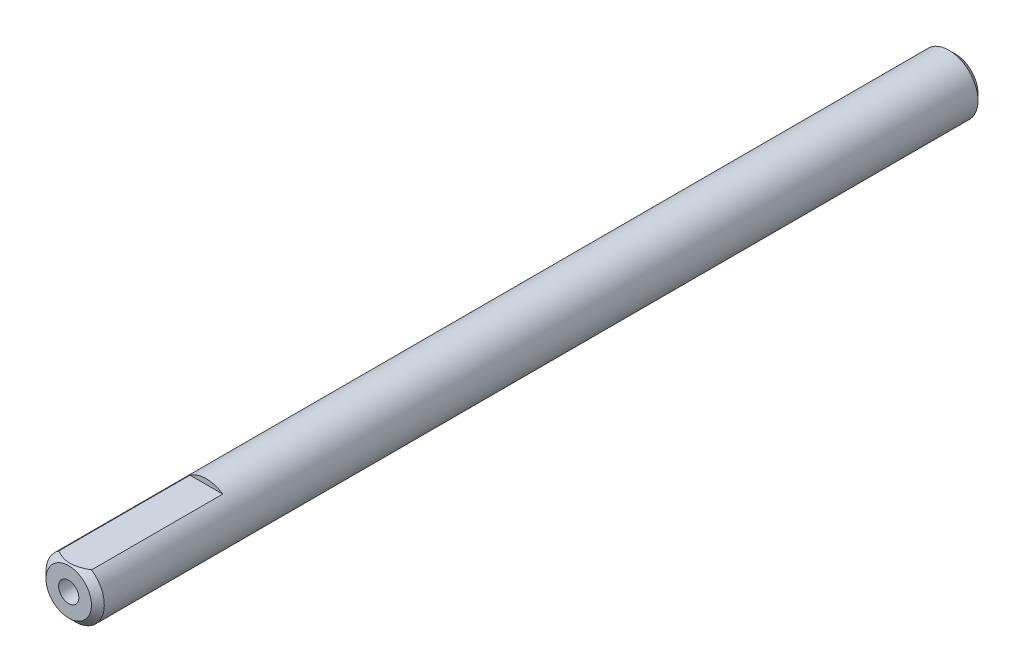
SolidWorks part; units mm, degrees
ref_plane "Ön Düzlem" through (0, 0, 0) normal (0, 0, 1) x (1, 0, 0)
ref_plane "Üst Düzlem" through (0, 0, 0) normal (0, 1, 0) x (1, 0, 0)
ref_plane "Sağ Düzlem" through (0, 0, 0) normal (1, 0, 0) x (0, 0, -1)
sketch "Çizim1" plane through (0, 0, 0) normal (0, 0, 1) x (1, 0, 0)
  circle A0 centre (0, 0) radius 3.175
  dimension "D1" = 6.35
extrude "Yükseklik-Ekstrüzyon1" add sketch "Çizim1" along normal blind 96.6
sketch "Çizim3" plane through (0, 0, 96.6) normal (0, 0, 1) x (1, 0, 0)
  circle A0 centre (0, 0) radius 1.1
  dimension "D1" = 2.2
extrude "Kes-Ekstrüzyon2" cut sketch "Çizim3" against normal blind 25
chamfer "Pah1" distance 0.7 angle 45 1 edges at (3.175, 0, 96.6)
chamfer "Pah2" distance 0.7 angle 45 1 edges at (3.175, 0, 0)
sketch "Esboço1" plane through (0, 0, 96.6) normal (0, 0, 1) x (1, 0, 0)
  line L0 (-1.7861, 2.625) -> (1.7861, 2.625)
  circle A0 centre (0, 0) radius 3.175 construction
  arc A1 (1.7861, 2.625) -> (-1.7861, 2.625) centre (0, 0) ccw
  dimension "D1" = 5.8
extrude "Corte-extrusão1" cut sketch "Esboço1" against normal blind 15
